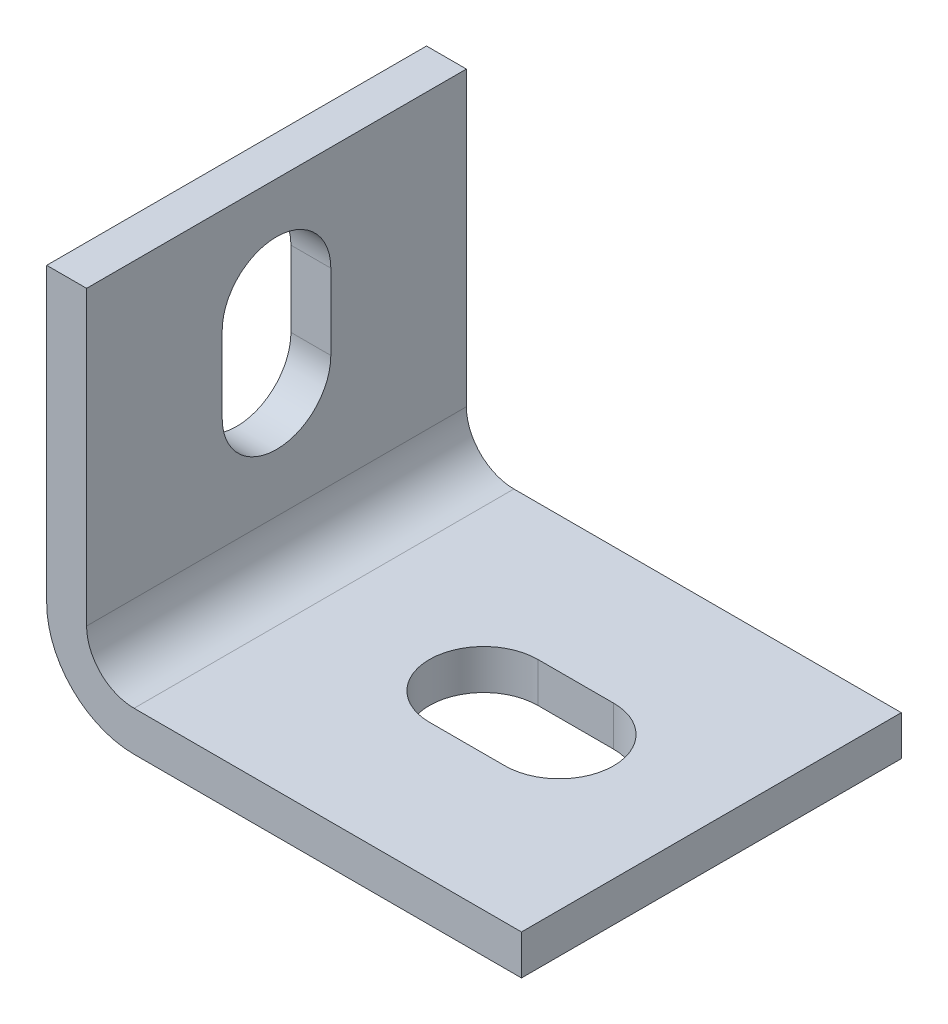
SolidWorks part; units mm, degrees
ref_plane "Front" through (0, 0, 0) normal (0, 0, 1) x (1, 0, 0)
ref_plane "Top" through (0, 0, 0) normal (0, 1, 0) x (1, 0, 0)
ref_plane "Right" through (0, 0, 0) normal (1, 0, 0) x (0, 0, -1)
sketch "Sketch2" plane through (0, 0, 0) normal (0, 0, 1) x (1, 0, 0)
  line L0 (0, 5.842) -> (0, 25.4)
  line L1 (5.842, 0) -> (31.75, 0)
  line L2 (5.842, 2.667) -> (31.75, 2.667)
  line L3 (2.667, 5.842) -> (2.667, 25.4)
  line L4 (0, 25.4) -> (2.667, 25.4)
  line L5 (31.75, 2.667) -> (31.75, 0)
  line L6 (2.667, 2.667) -> (31.75, 2.667) construction
  line L7 (2.667, 2.667) -> (2.667, 25.4) construction
  line L8 (0, 0) -> (0, 25.4) construction
  line L9 (0, 0) -> (31.75, 0) construction
  arc A0 (5.842, 2.667) -> (2.667, 5.842) centre (5.842, 5.842) cw
  arc A1 (0, 5.842) -> (5.842, 0) centre (5.842, 5.842) ccw
  point P13 (0, 0)
  dimension "D4" = 3.175
  dimension "D5" = 5.842
  dimension "D2" = 31.75
  dimension "D3" = 25.4
  dimension "D1" = 2.667
extrude "Boss-Extrude1" add sketch "Sketch2" along normal blind 25.4
sketch "Sketch3" plane through (2.667, 0, 0) normal (1, 0, 0) x (0, 0, -1)
  line L0 (-12.7, 25.4) -> (-12.7, 0) construction
  line L1 (-25.4, 25.4) -> (0, 25.4) construction
  line L2 (-25.4, 0) -> (0, 0) construction
  line L3 (-12.7, 18.4023) -> (-12.7, 13.3477) construction
  line L4 (-9.0678, 18.4023) -> (-9.0678, 13.3477)
  line L5 (-16.3322, 18.4023) -> (-16.3322, 13.3477)
  arc A0 (-9.0678, 18.4023) -> (-16.3322, 18.4023) centre (-12.7, 18.4023) ccw
  arc A1 (-16.3322, 13.3477) -> (-9.0678, 13.3477) centre (-12.7, 13.3477) ccw
  point P8 (-12.7, 15.875)
  dimension "D2" = 12.319
  dimension "D1" = 7.2644
  dimension "D3" = 9.525
extrude "Cut-Extrude1" cut sketch "Sketch3" against normal through all
sketch "Sketch4" plane through (0, 2.667, 0) normal (0, 1, 0) x (1, 0, 0)
  line L0 (21.5773, -12.7) -> (16.5227, -12.7) construction
  line L1 (21.5773, -16.3322) -> (16.5227, -16.3322)
  line L2 (21.5773, -9.0678) -> (16.5227, -9.0678)
  line L3 (31.75, -12.7) -> (0, -12.7) construction
  line L4 (31.75, -25.4) -> (31.75, 0) construction
  line L5 (0, -25.4) -> (0, 0) construction
  arc A0 (21.5773, -16.3322) -> (21.5773, -9.0678) centre (21.5773, -12.7) ccw
  arc A1 (16.5227, -9.0678) -> (16.5227, -16.3322) centre (16.5227, -12.7) ccw
  point P2 (19.05, -12.7)
  dimension "D1" = 12.319
  dimension "D2" = 7.2644
  dimension "D3" = 12.7
extrude "Cut-Extrude2" cut sketch "Sketch4" against normal through all
equation "\"D5@Sketch2\"=\"D4@Sketch2\"+.105"
